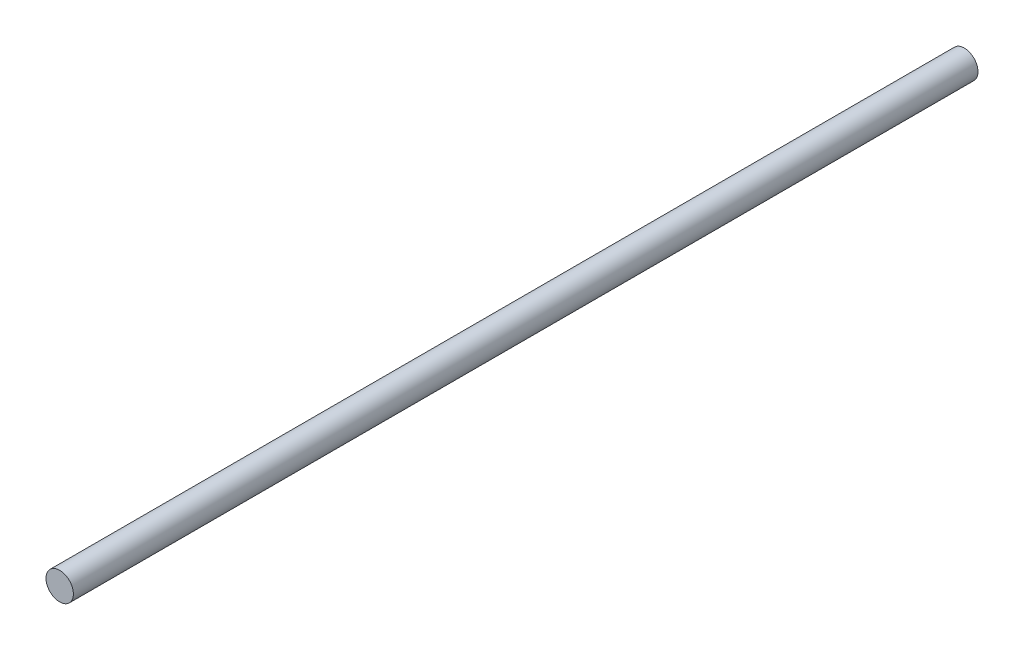
SolidWorks part; units mm, degrees
ref_plane "Ebene vorne" through (0, 0, 0) normal (0, 0, 1) x (1, 0, 0)
ref_plane "Ebene oben" through (0, 0, 0) normal (0, 1, 0) x (1, 0, 0)
ref_plane "Ebene rechts" through (0, 0, 0) normal (1, 0, 0) x (0, 0, -1)
sketch "Sketch1" plane through (0, 0, 0) normal (0, 0, 1) x (1, 0, 0)
  circle A0 centre (0, 0) radius 4
  dimension "D1" = 8
extrude "Boss-Extrude1" add sketch "Sketch1" along normal blind 264
